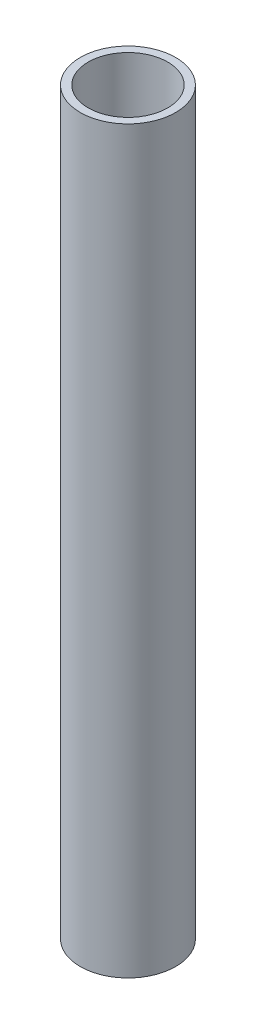
SolidWorks part; units mm, degrees
ref_plane "Front Plane" through (0, 0, 0) normal (0, 0, 1) x (1, 0, 0)
ref_plane "Top Plane" through (0, 0, 0) normal (0, 1, 0) x (1, 0, 0)
ref_plane "Right Plane" through (0, 0, 0) normal (1, 0, 0) x (0, 0, -1)
sketch "Sketch1" plane through (0, 0, 0) normal (0, 1, 0) x (1, 0, 0)
  circle A0 centre (0, 0) radius 6
  circle A1 centre (0, 0) radius 5
  dimension "D1" = 12
  dimension "D2" = 1
extrude "Boss-Extrude1" add sketch "Sketch1" along normal blind 93
